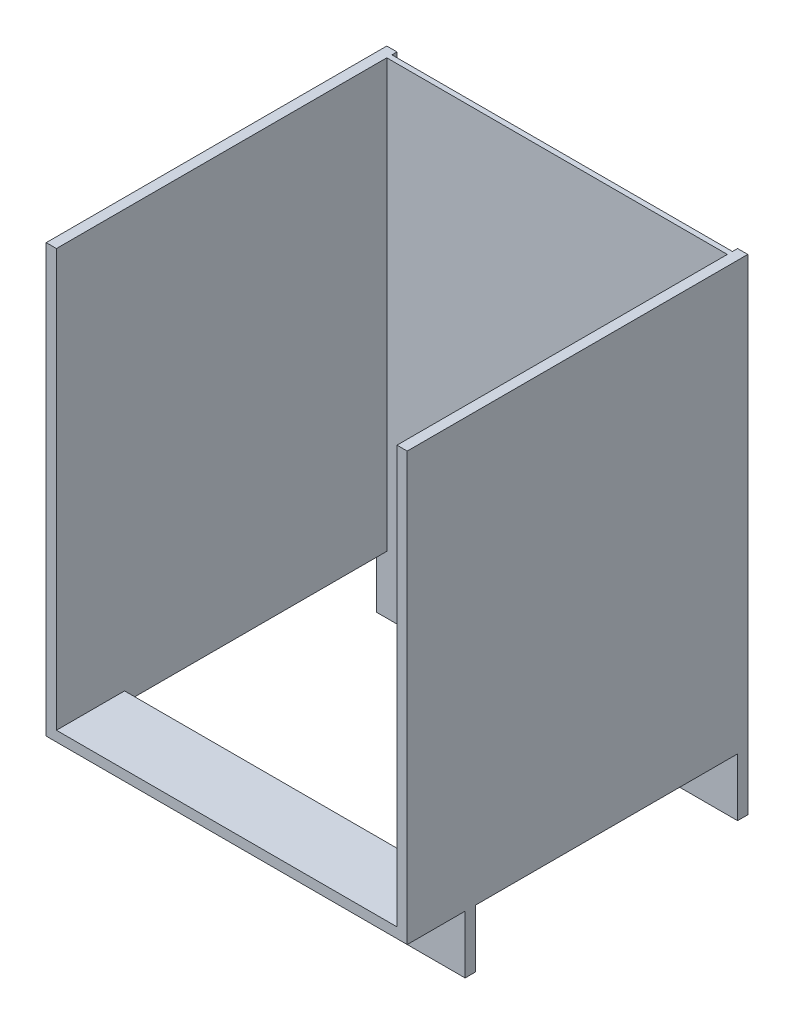
SolidWorks part; units mm, degrees
ref_plane "Front" through (0, 0, 0) normal (0, 0, 1) x (1, 0, 0)
ref_plane "Top" through (0, 0, 0) normal (0, 1, 0) x (1, 0, 0)
ref_plane "Right" through (0, 0, 0) normal (1, 0, 0) x (0, 0, -1)
sketch "Sketch2" plane through (0, 0, 0) normal (0, 0, 1) x (1, 0, 0)
  line L1 (0, 0) -> (636, 0)
  line L2 (0, 0) -> (0, 753)
  line L3 (0, 753) -> (636, 753)
  line L4 (636, 0) -> (636, 753)
  dimension "D1" = 636
  dimension "D2" = 753
extrude "Boss-Extrude1" add sketch "Sketch2" along normal blind 600
sketch "Sketch3" plane through (0, 0, 600) normal (0, 0, 1) x (1, 0, 0)
  line L0 (636, 753) -> (0, 753) construction
  line L1 (18, 753) -> (618, 753)
  line L2 (18, 753) -> (18, 18)
  line L3 (18, 18) -> (618, 18)
  line L4 (618, 753) -> (618, 18)
  line L5 (0, 0) -> (636, 0) construction
  line L6 (636, 0) -> (636, 753) construction
  line L7 (0, 753) -> (0, 0) construction
  dimension "D1" = 18
  dimension "D2" = 18
  dimension "D3" = 18
extrude "Cut-Extrude1" cut sketch "Sketch3" against normal up to surface (600 mm away) up to face at (318, 376.5, 0)
sketch "Sketch4" plane through (0, 0, 0) normal (0, 0, -1) x (-1, 0, 0)
  line L1 (-618, 753) -> (-18, 753)
  line L2 (-618, 753) -> (-618, 18)
  line L3 (-618, 18) -> (-18, 18)
  line L4 (-18, 753) -> (-18, 18)
extrude "Boss-Extrude2" add sketch "Sketch4" along normal blind 9 from offset 18 offset against normal yes
sketch "Sketch5" plane through (0, 0, 600) normal (0, 0, 1) x (1, 0, 0)
  line L0 (636, 0) -> (636, 753) construction
  line L1 (0, 0) -> (636, 0)
  line L2 (0, 0) -> (0, -102)
  line L3 (0, -102) -> (636, -102)
  line L4 (636, 0) -> (636, -102)
  dimension "D1" = 102
extrude "Boss-Extrude3" add sketch "Sketch5" against normal blind 18 from offset 102 offset against normal yes
sketch "Sketch6" plane through (0, 0, 0) normal (0, 0, -1) x (-1, 0, 0)
  line L1 (-636, 0) -> (0, 0)
  line L2 (-636, 0) -> (-636, -102)
  line L3 (-636, -102) -> (0, -102)
  line L4 (0, 0) -> (0, -102)
extrude "Boss-Extrude4" add sketch "Sketch6" against normal blind 18
sketch "Sketch7" plane through (0, 0, 0) normal (0, -1, 0) x (1, 0, 0)
  line L0 (636, 480) -> (0, 480) construction
  line L1 (18, 480) -> (618, 480)
  line L2 (18, 480) -> (18, 18)
  line L3 (18, 18) -> (618, 18)
  line L4 (618, 480) -> (618, 18)
  line L5 (636, 18) -> (0, 18) construction
  line L6 (0, 480) -> (0, 18) construction
  line L7 (636, 480) -> (636, 18) construction
  dimension "D1" = 18
  dimension "D2" = 18
extrude "Cut-Extrude2" cut sketch "Sketch7" against normal up to next
